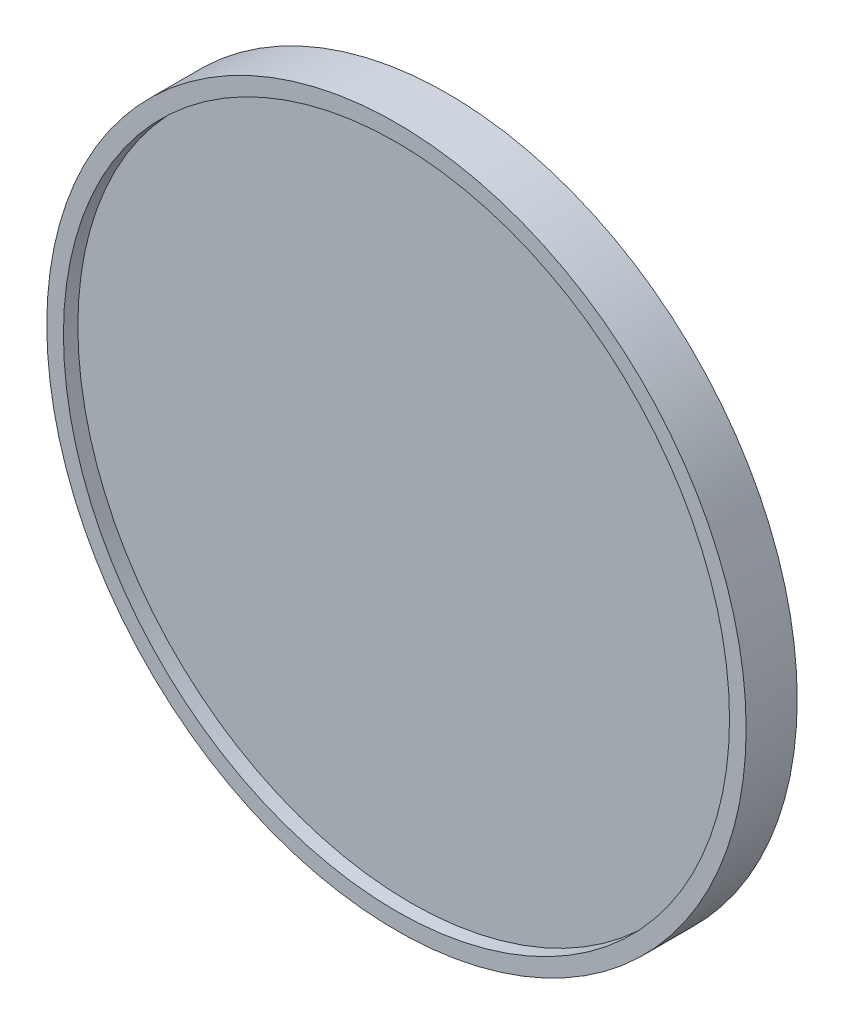
SolidWorks part; units mm, degrees
ref_plane "정면" through (0, 0, 0) normal (0, 0, 1) x (1, 0, 0)
ref_plane "윗면" through (0, 0, 0) normal (0, 1, 0) x (1, 0, 0)
ref_plane "우측면" through (0, 0, 0) normal (1, 0, 0) x (0, 0, -1)
sketch "스케치1" plane through (0, 0, 0) normal (0, 0, 1) x (1, 0, 0)
  circle A0 centre (0, 0) radius 31.5
extrude "보스-돌출1" add sketch "스케치1" along normal blind 2
sketch "스케치2" plane through (0, 0, 2) normal (0, 0, 1) x (1, 0, 0)
  circle A0 centre (0, 0) radius 31.5
  circle A1 centre (0, 0) radius 30
extrude "보스-돌출2" add sketch "스케치2" along normal blind 1.3
sketch "스케치3" plane through (0, 0, 0) normal (0, 0, -1) x (-1, 0, 0)
  circle A0 centre (0, 0) radius 31.5
  circle A1 centre (0, 0) radius 30
extrude "보스-돌출3" add sketch "스케치3" along normal blind 1.3
